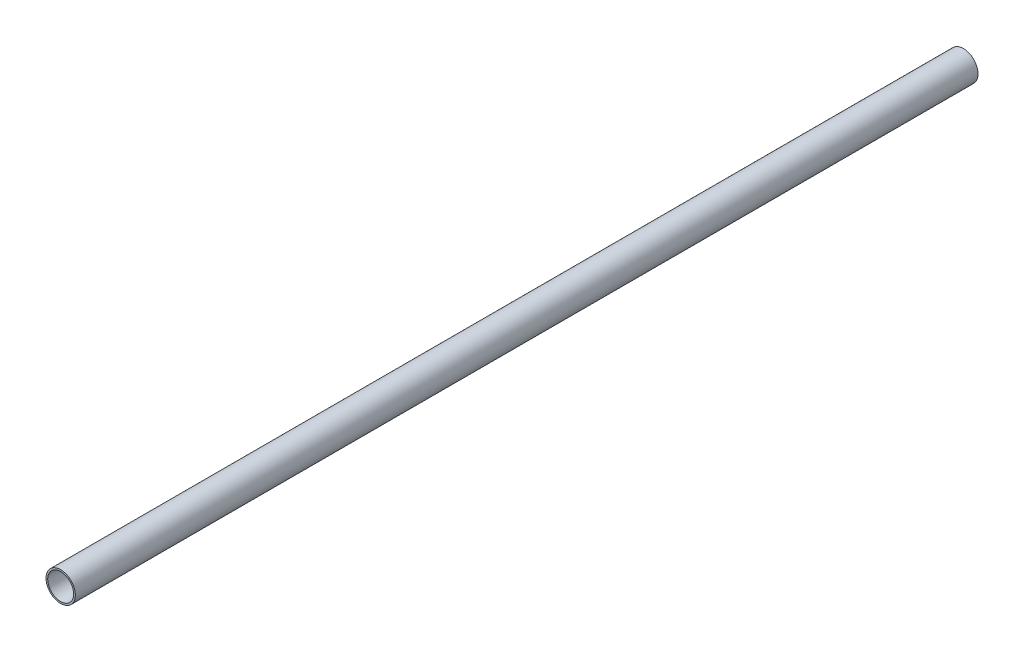
SolidWorks part; units mm, degrees
material "Thornel Mat VMA"
ref_plane "Front Plane" through (0, 0, 0) normal (0, 0, 1) x (1, 0, 0)
ref_plane "Top Plane" through (0, 0, 0) normal (0, 1, 0) x (1, 0, 0)
ref_plane "Right Plane" through (0, 0, 0) normal (1, 0, 0) x (0, 0, -1)
sketch "Sketch1" plane through (0, 0, 0) normal (0, 0, 1) x (1, 0, 0)
  circle A0 centre (0, 0) radius 6.5
  circle A1 centre (0, 0) radius 5.75
  dimension "D1" = 13
  dimension "D2" = 11.5
extrude "Boss-Extrude1" add sketch "Sketch1" along normal mid plane 400.05
